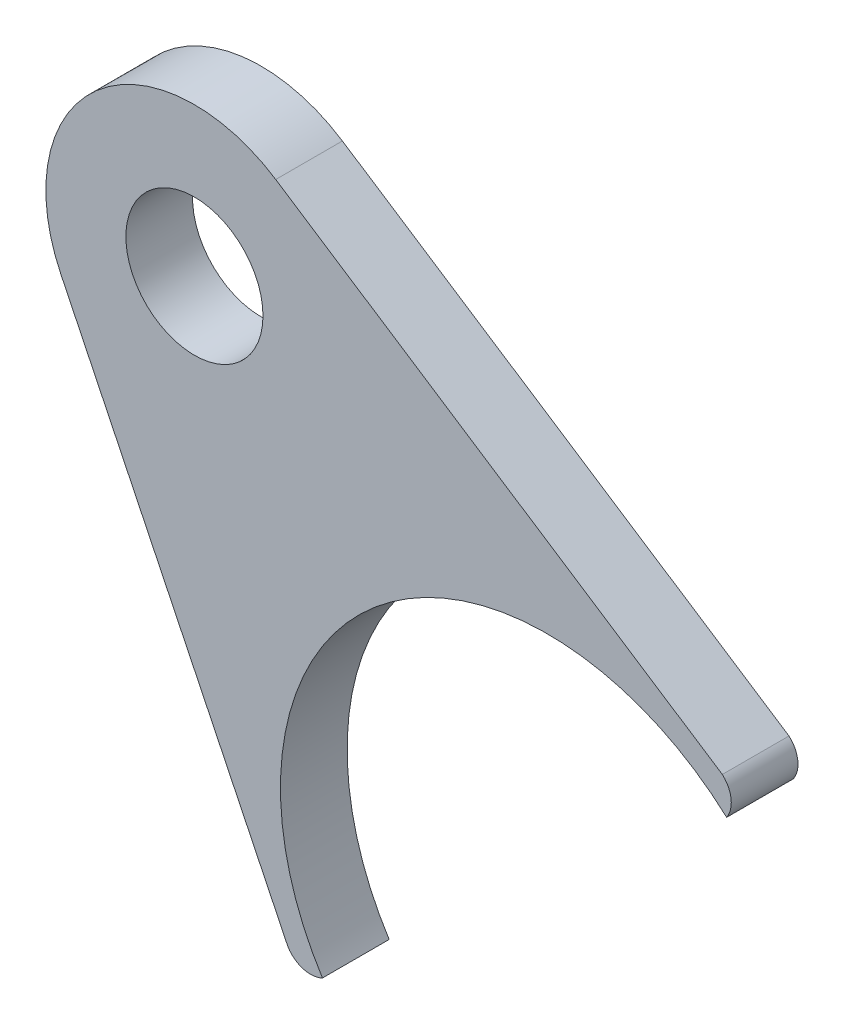
SolidWorks part; units mm, degrees
ref_plane "Front Plane" through (0, 0, 0) normal (0, 0, 1) x (1, 0, 0)
ref_plane "Top Plane" through (0, 0, 0) normal (0, 1, 0) x (1, 0, 0)
ref_plane "Right Plane" through (0, 0, 0) normal (1, 0, 0) x (0, 0, -1)
sketch "Sketch1" plane through (0, 0, 0) normal (0, 0, 1) x (1, 0, 0)
  line L0 (8.3328, 11.07) -> (-12.9296, 24.9708) construction
  line L1 (-12.3465, -6.379) -> (-23.1672, 15.967) construction
  line L2 (8.3328, 11.07) -> (-12.9296, 24.9708)
  line L3 (-12.3465, -6.379) -> (-23.1672, 15.967)
  arc A1 (8.5406, 9.4054) -> (8.3328, 11.07) centre (7.4904, 10.1196) ccw construction
  circle A2 centre (-16.8005, 19.05) radius 3.2639
  circle A3 centre (-16.8005, 19.05) radius 3.2639
  circle A4 centre (0, 0) radius 12.7045
  arc A5 (8.5406, 9.4054) -> (-10.7046, -6.8422) centre (0, 0) ccw
  arc A6 (-12.9296, 24.9708) -> (-23.1672, 15.967) centre (-16.8005, 19.05) ccw construction
  arc A7 (-12.3465, -6.379) -> (-10.7046, -6.8422) centre (-11.2701, -5.705) ccw construction
  arc A8 (8.5406, 9.4054) -> (8.3328, 11.07) centre (7.4904, 10.1196) ccw
  arc A9 (-12.9296, 24.9708) -> (-23.1672, 15.967) centre (-16.8005, 19.05) ccw
  arc A10 (-12.3465, -6.379) -> (-10.7046, -6.8422) centre (-11.2701, -5.705) ccw
  dimension "D1" = 0
  dimension "D2" = 0
extrude "Boss-Extrude1" add sketch "Sketch1" along normal blind 3.175
